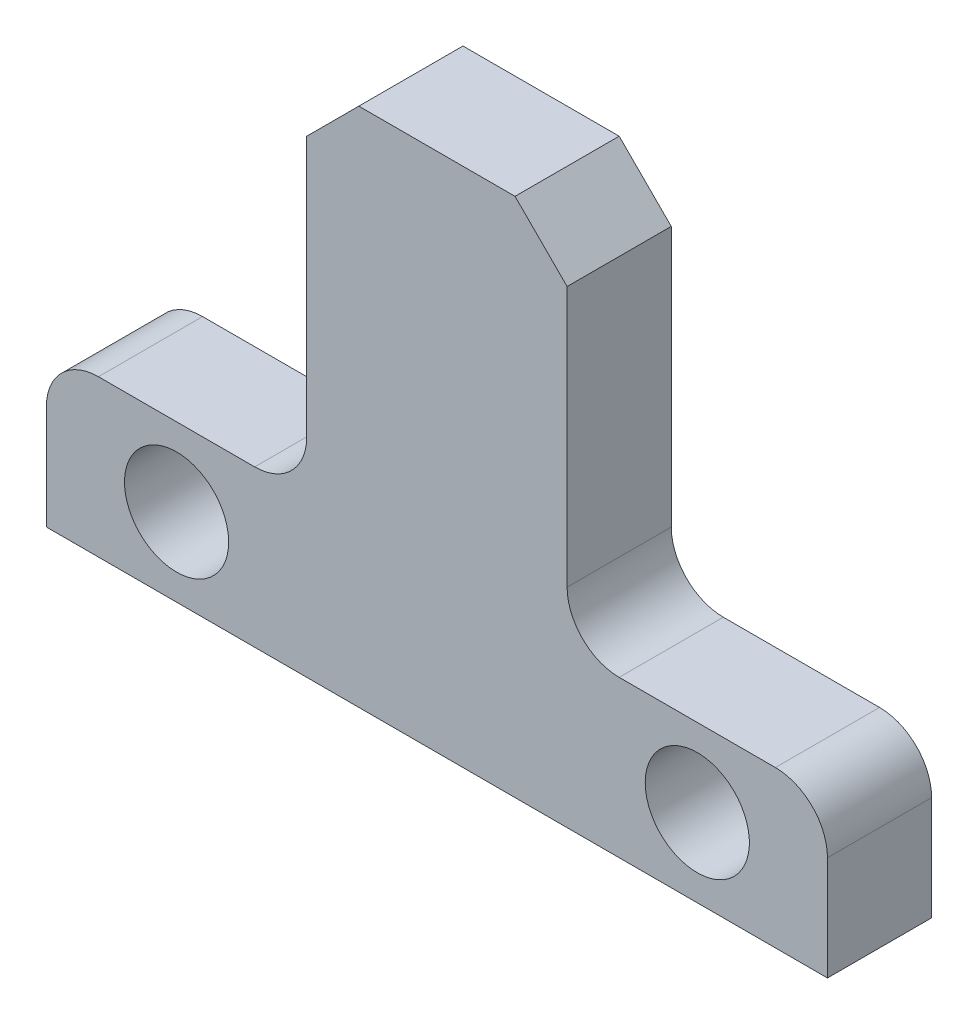
SolidWorks part; units mm, degrees
ref_plane "Front Plane" through (0, 0, 0) normal (0, 0, 1) x (1, 0, 0)
ref_plane "Top Plane" through (0, 0, 0) normal (0, 1, 0) x (1, 0, 0)
ref_plane "Right Plane" through (0, 0, 0) normal (1, 0, 0) x (0, 0, -1)
sketch "Sketch1" plane through (0, 0, 0) normal (0, 0, 1) x (1, 0, 0)
  line L0 (-75, 0) -> (75, 0)
  line L1 (-75, 0) -> (-75, 20)
  line L2 (-65, 30) -> (-35, 30)
  line L3 (-25, 40) -> (-25, 90)
  line L5 (75, 0) -> (75, 20)
  line L6 (65, 30) -> (35, 30)
  line L7 (-25, 90) -> (-15, 100)
  line L8 (-15, 100) -> (15, 100)
  line L9 (25, 40) -> (25, 90)
  line L10 (25, 90) -> (15, 100)
  arc A0 (-65, 30) -> (-75, 20) centre (-65, 20) ccw
  arc A1 (-25, 40) -> (-35, 30) centre (-35, 40) cw
  circle A2 centre (-50, 15) radius 10
  circle A3 centre (50, 15) radius 10
  arc A4 (65, 30) -> (75, 20) centre (65, 20) cw
  arc A5 (25, 40) -> (35, 30) centre (35, 40) ccw
  point P4 (0, 0)
  point P20 (0, 0)
  point P28 (0, 100)
  dimension "D1" = 10
  dimension "D2" = 10
extrude "Boss-Extrude1" add sketch "Sketch1" along normal blind 20
